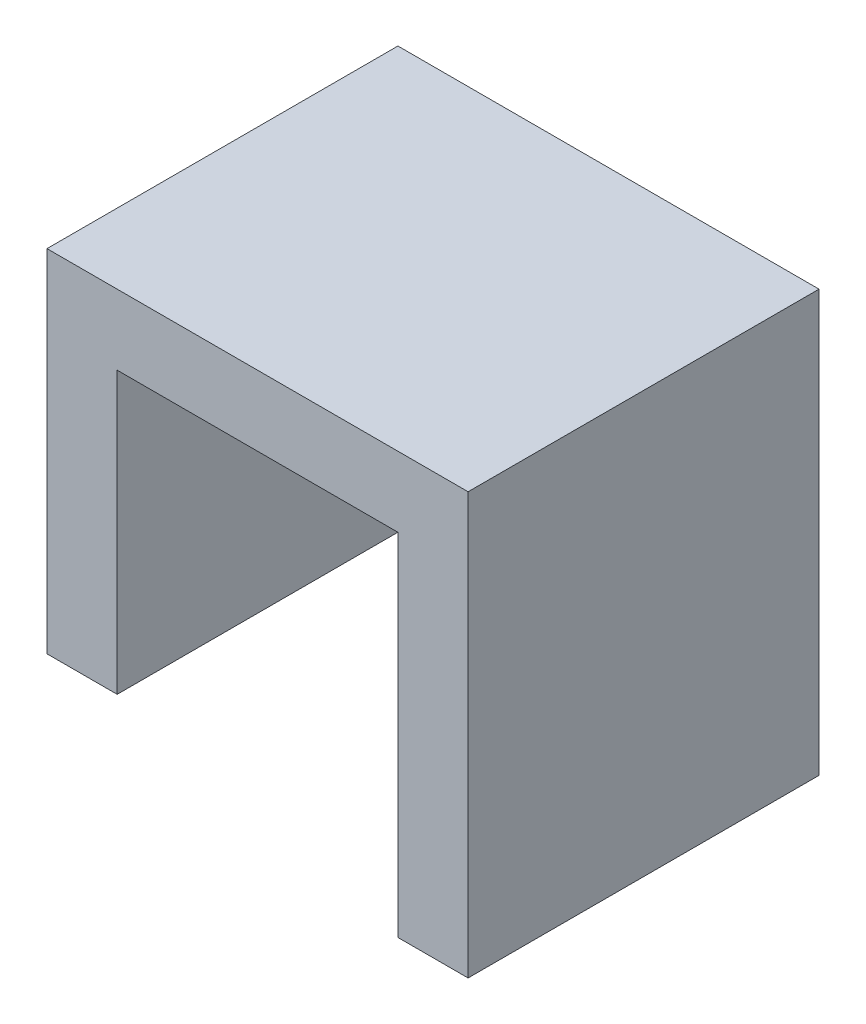
SolidWorks part; units mm, degrees
ref_plane "Front Plane" through (0, 0, 0) normal (0, 0, 1) x (1, 0, 0)
ref_plane "Top Plane" through (0, 0, 0) normal (0, 1, 0) x (1, 0, 0)
ref_plane "Right Plane" through (0, 0, 0) normal (1, 0, 0) x (0, 0, -1)
sketch "Sketch1" plane through (0, 0, 0) normal (0, 1, 0) x (1, 0, 0)
  line L1 (-3.1268, 3.5352) -> (-1.1268, 3.5352)
  line L2 (-3.1268, 3.5352) -> (-3.1268, -6.4648)
  line L3 (-3.1268, -6.4648) -> (-1.1268, -6.4648)
  line L4 (-1.1268, 3.5352) -> (-1.1268, -6.4648)
  dimension "D1" = 2
  dimension "D2" = 10
extrude "Boss-Extrude1" add sketch "Sketch1" along normal blind 10
sketch "Sketch2" plane through (-1.1268, 0, 0) normal (1, 0, 0) x (0, 0, -1)
  line L0 (3.5352, 10) -> (3.5352, 0) construction
  line L1 (-6.4648, 10) -> (3.5352, 10)
  line L2 (-6.4648, 10) -> (-6.4648, 8)
  line L3 (-6.4648, 8) -> (3.5352, 8)
  line L4 (3.5352, 10) -> (3.5352, 8)
  dimension "D1" = 2
extrude "Boss-Extrude2" add sketch "Sketch2" along normal blind 10
sketch "Sketch3" plane through (0, 8, 0) normal (0, -1, 0) x (1, 0, 0)
  line L0 (8.8732, -3.5352) -> (-1.1268, -3.5352) construction
  line L1 (8.8732, 6.4648) -> (6.8732, 6.4648)
  line L2 (8.8732, 6.4648) -> (8.8732, -3.5352)
  line L3 (8.8732, -3.5352) -> (6.8732, -3.5352)
  line L4 (6.8732, 6.4648) -> (6.8732, -3.5352)
  dimension "D1" = 2
extrude "Boss-Extrude3" add sketch "Sketch3" along normal blind 10 contours L4 L3 L2 L1
